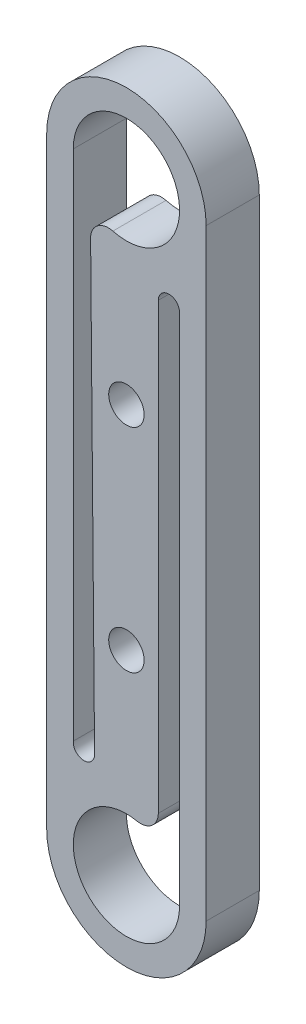
SolidWorks part; units mm, degrees
ref_plane "前视基准面" through (0, 0, 0) normal (0, 0, 1) x (1, 0, 0)
ref_plane "上视基准面" through (0, 0, 0) normal (0, 1, 0) x (1, 0, 0)
ref_plane "右视基准面" through (0, 0, 0) normal (1, 0, 0) x (0, 0, -1)
sketch "草图1" plane through (0, 0, 0) normal (0, 0, 1) x (1, 0, 0)
  line L0 (-472.8734, 72.7562) -> (-472.8734, 47.6756)
  line L1 (-471.6728, 43.7562) -> (-471.6722, 72.7562)
  line L2 (-476.4706, 48.7562) -> (-476.6944, 73.88)
  line L3 (-477.6728, 77.7562) -> (-477.6728, 48.8076)
  line L4 (-470.1728, 43.7562) -> (-470.1728, 77.7562)
  line L5 (-479.1728, 77.7562) -> (-479.1728, 43.7562)
  line L6 (-466.7026, 60.7562) -> (-485.1617, 60.7562) construction
  arc A0 (-471.6722, 72.7562) -> (-472.8734, 72.7562) centre (-472.2728, 72.7562) ccw
  arc A1 (-474.0732, 46.6957) -> (-472.8734, 47.6756) centre (-473.8734, 47.6756) ccw
  arc A2 (-474.0732, 46.6957) -> (-471.6728, 43.7562) centre (-474.6728, 43.7562) ccw
  arc A3 (-477.6728, 48.8076) -> (-476.4706, 48.7562) centre (-477.0728, 48.7562) ccw
  arc A4 (-475.4391, 74.8558) -> (-476.6944, 73.88) centre (-475.6945, 73.8889) ccw
  arc A5 (-475.4391, 74.8558) -> (-477.6728, 77.7562) centre (-474.6728, 77.7562) ccw
  arc A6 (-479.1728, 43.7562) -> (-470.1728, 43.7562) centre (-474.6728, 43.7562) ccw
  arc A7 (-470.1728, 77.7562) -> (-479.1728, 77.7562) centre (-474.6728, 77.7562) ccw
  circle A8 centre (-474.6728, 60.7562) radius 1 construction
  circle A9 centre (-474.6728, 66.7562) radius 1
  circle A10 centre (-474.6728, 54.7562) radius 1
  dimension "D3" = 1
  dimension "D5" = 3
  dimension "D6" = 1
  dimension "D7" = 2
  dimension "D8" = 2
  dimension "D9" = 2
  dimension "D1" = 34
  dimension "D2" = 29
  dimension "D4" = 29
  dimension "D10" = 6
  dimension "D11" = 6
extrude "凸台-拉伸1" add sketch "草图1" along normal blind 3
